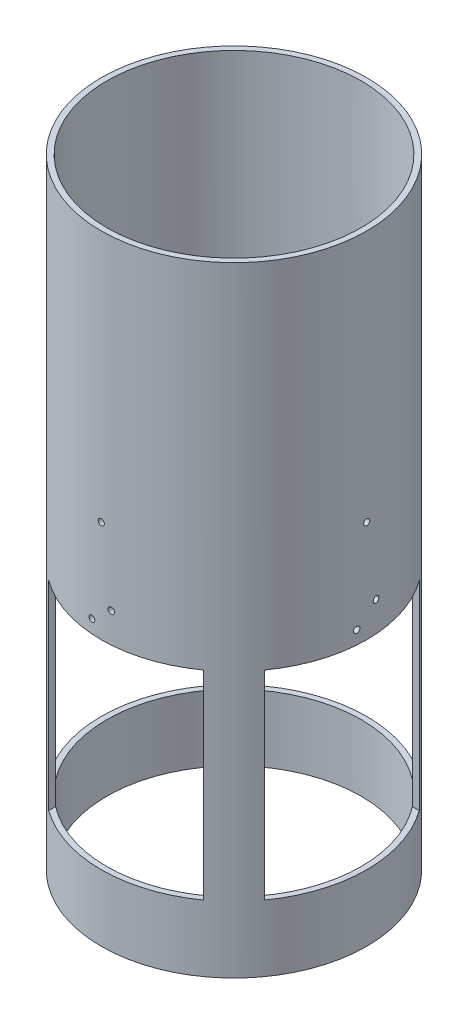
SolidWorks part; units mm, degrees
ref_plane "Front Plane" through (0, 0, 0) normal (0, 0, 1) x (1, 0, 0)
ref_plane "Top Plane" through (0, 0, 0) normal (0, 1, 0) x (1, 0, 0)
ref_plane "Right Plane" through (0, 0, 0) normal (1, 0, 0) x (0, 0, -1)
sketch "Sketch1" plane through (0, 0, 0) normal (0, 1, 0) x (1, 0, 0)
  circle A0 centre (0, 0) radius 76.2
  circle A1 centre (0, 0) radius 73.025
extrude "Boss-Extrude1" add sketch "Sketch1" along normal blind 330.2
sketch "Sketch5" plane through (0, 0, 0) normal (0, -1, 0) x (1, 0, 0)
  line L0 (0, 76.2) -> (0, -76.2) construction
  circle A0 centre (0, 0) radius 76.2 construction
ref_plane "Plane2" through (0, 0, -76.2) normal (0, 0, -1) x (-1, 0, 0)
sketch "Sketch6" plane through (0, 0, -76.2) normal (0, 0, -1) x (-1, 0, 0)
  line L0 (0, 330.2) -> (0, 127) construction
  line L1 (73.025, 330.2) -> (-73.025, 330.2) construction
  line L2 (-44.45, 127) -> (44.45, 127)
  line L13 (44.45, 127) -> (44.45, 12.7)
  line L16 (-44.45, 12.7) -> (44.45, 12.7)
  line L17 (-44.45, 127) -> (-44.45, 12.7)
  point P15 (0, 127)
extrude "Cut-Extrude6" cut sketch "Sketch6" against normal blind 20.574
pattern_circular "CirPattern9" count 4 over 360 about axis through (0, 0, 0) along (0, 1, 0) of "Cut-Extrude6"
sketch "Sketch7" plane through (0, 0, -76.2) normal (0, 0, -1) x (-1, 0, 0)
  line L0 (0, 0) -> (0, 127) construction
  line L1 (0, 127) -> (0, 134.62) construction
  line L2 (0, 127) -> (0, 144.145) construction
  line L3 (0, 127) -> (0, 185.42) construction
  line L4 (0, 134.62) -> (-5.5562, 134.62) construction
  line L5 (0, 144.145) -> (5.5562, 144.145) construction
  circle A2 centre (0, 185.42) radius 1.7526
  circle A3 centre (5.5562, 144.145) radius 1.7526
  circle A4 centre (-5.5562, 134.62) radius 1.7526
  point P6 (0, 134.62)
extrude "Cut-Extrude7" cut sketch "Sketch7" against normal blind 17.78 contours A4 | A3 | A2
pattern_circular "CirPattern10" count 4 over 360 about axis through (0, 330.2, 0) along (0, 1, 0) of "Cut-Extrude7"
sketch "Sketch8" plane through (0, 0, 0) normal (0, -1, 0) x (1, 0, 0)
  circle A0 centre (0, 0) radius 76.2
  circle A1 centre (0, 0) radius 73.025
extrude "Boss-Extrude2" add sketch "Sketch8" along normal blind 25.4
